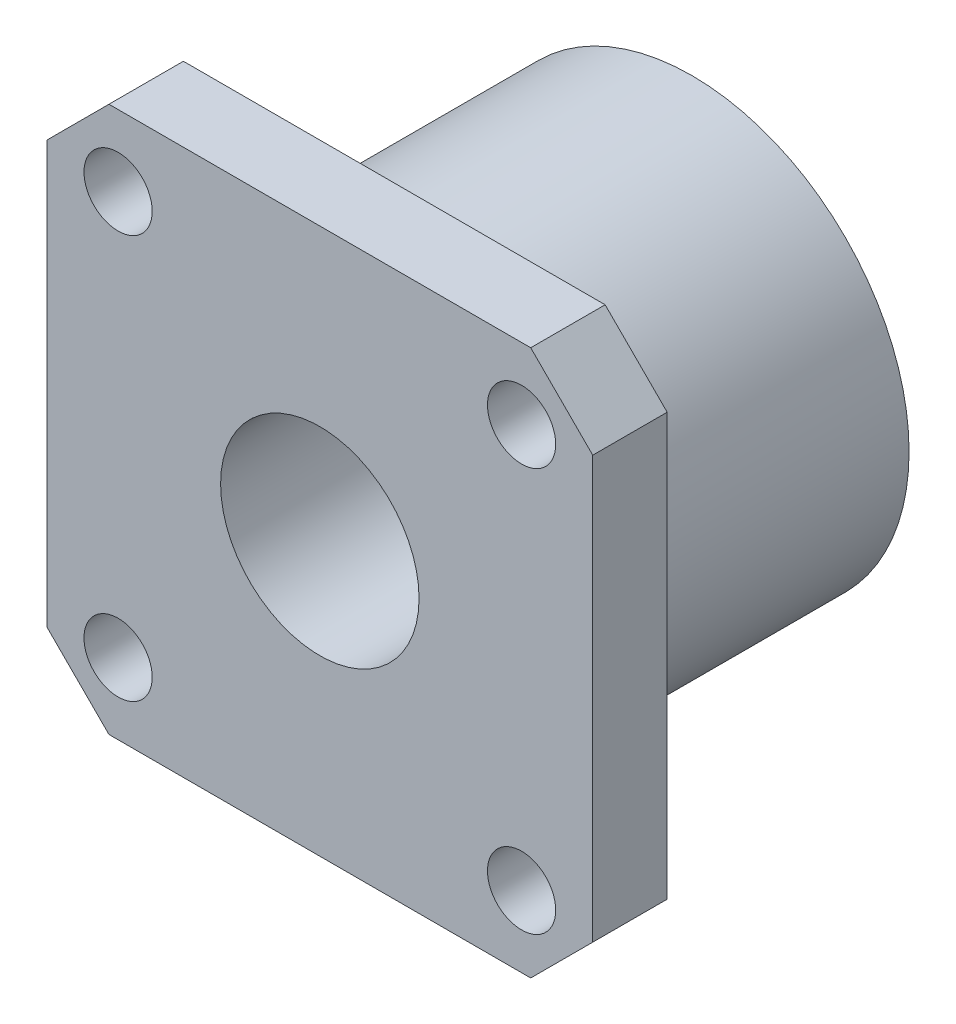
SolidWorks part; units mm, degrees
ref_plane "前视基准面" through (0, 0, 0) normal (0, 0, 1) x (1, 0, 0)
ref_plane "上视基准面" through (0, 0, 0) normal (0, 1, 0) x (1, 0, 0)
ref_plane "右视基准面" through (0, 0, 0) normal (1, 0, 0) x (0, 0, -1)
sketch "草图1" plane through (0, 0, 0) normal (0, 0, 1) x (1, 0, 0)
  line L1 (22, -22) -> (-22, -22)
  line L2 (22, -22) -> (22, 22)
  line L3 (22, 22) -> (-22, 22)
  line L4 (-22, -22) -> (-22, 22)
  line L5 (22, -22) -> (-22, 22) construction
  line L6 (22, 22) -> (-22, -22) construction
  circle A0 centre (-16.2635, 16.2635) radius 2.75
  circle A2 centre (16.2635, 16.2635) radius 2.75
  circle A3 centre (16.2635, -16.2635) radius 2.75
  circle A4 centre (-16.2635, -16.2635) radius 2.75
  point P0 (0, 0)
  dimension "D2" = 5.5
  dimension "D3" = 23
  dimension "D1" = 44
  dimension "D4" = 4
extrude "凸台-拉伸1" add sketch "草图1" along normal blind 6
chamfer "倒角1" distance 5 angle 45 4 edges at (-22, -22, 3) (22, -22, 3) (22, 22, 3) (-22, 22, 3)
sketch "草图2" plane through (0, 0, 0) normal (0, 0, -1) x (-1, 0, 0)
  circle A0 centre (0, 0) radius 17.5
  circle A1 centre (0, 0) radius 8
  dimension "D1" = 35
  dimension "D2" = 16
extrude "凸台-拉伸2" add sketch "草图2" along normal blind 24
sketch "草图3" plane through (0, 0, 0) normal (0, 0, -1) x (-1, 0, 0)
  circle A1 centre (0, 0) radius 8
  circle A3 centre (0, 0) radius 8
  dimension "D1" = 0
extrude "切除-拉伸1" cut sketch "草图3" against normal through all
